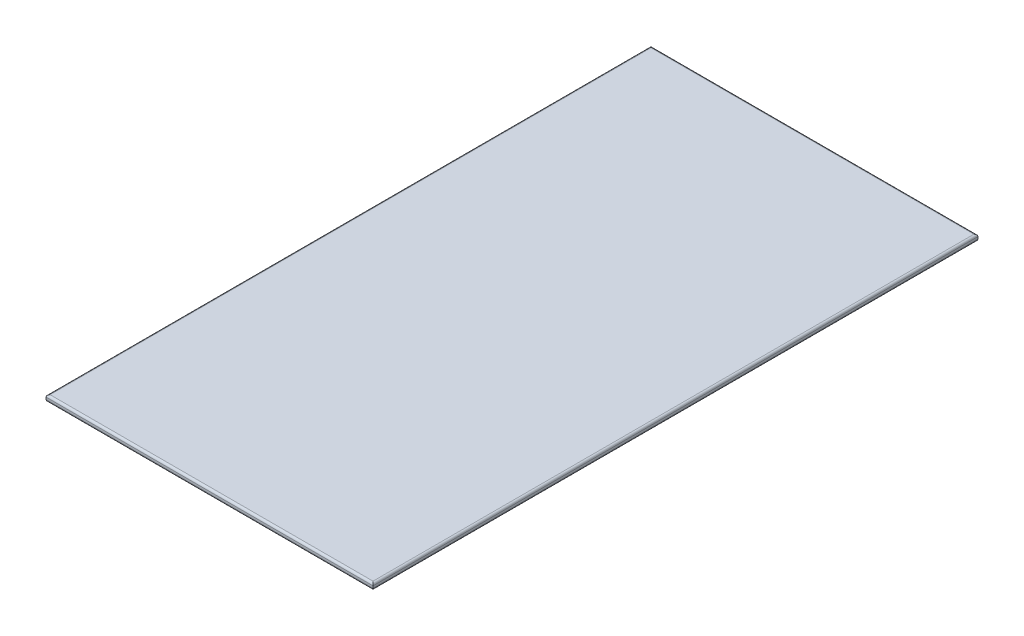
SolidWorks part; units mm, degrees
ref_plane "Front" through (0, 0, 0) normal (0, 0, 1) x (1, 0, 0)
ref_plane "Top" through (0, 0, 0) normal (0, 1, 0) x (1, 0, 0)
ref_plane "Right" through (0, 0, 0) normal (1, 0, 0) x (0, 0, -1)
sketch "Sketch1" plane through (0, 0, 0) normal (0, 1, 0) x (1, 0, 0)
  line L1 (-80, 148) -> (80, 148)
  line L2 (-80, 148) -> (-80, -148)
  line L3 (-80, -148) -> (80, -148)
  line L4 (80, 148) -> (80, -148)
  line L5 (-80, 148) -> (80, -148) construction
  line L6 (-80, -148) -> (80, 148) construction
  point P0 (0, 0)
  dimension "D1" = 160
  dimension "D2" = 296
extrude "Boss-Extrude1" add sketch "Sketch1" along normal blind 3
fillet "Fillet1" radius 1 8 edges at (0, 0, -148) (-80, 0, 0) (0, 0, 148) (80, 0, 0) (0, 3, 148) (-80, 3, 0) (0, 3, -148) (80, 3, 0)
